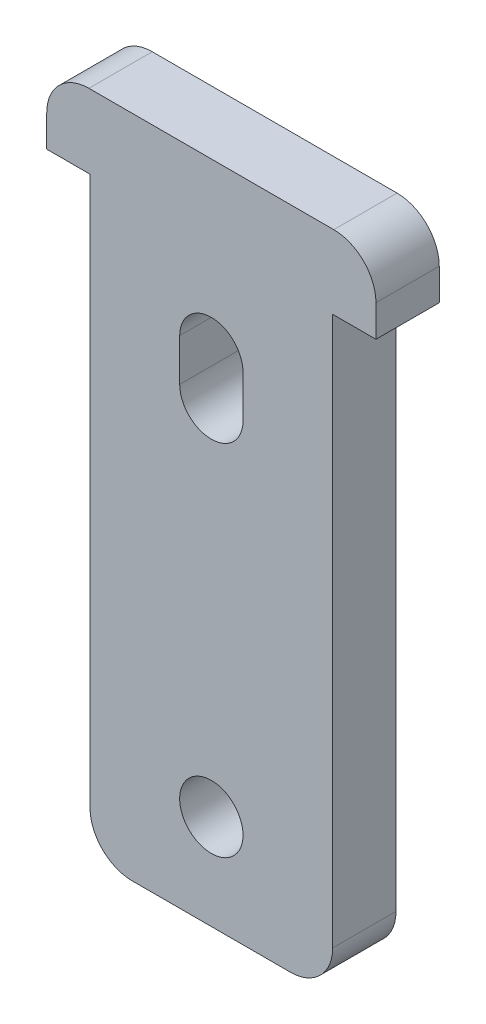
SolidWorks part; units mm, degrees
ref_plane "Plano frontal" through (0, 0, 0) normal (0, 0, 1) x (1, 0, 0)
ref_plane "Plano superior" through (0, 0, 0) normal (0, 1, 0) x (1, 0, 0)
ref_plane "Plano direito" through (0, 0, 0) normal (1, 0, 0) x (0, 0, -1)
sketch "Esboço1" plane through (0, 0, 0) normal (0, 0, 1) x (1, 0, 0)
  line L0 (11.5, 28) -> (13.55, 28)
  line L1 (0, 0) -> (11.5, 0)
  line L2 (0, 0) -> (0, 28)
  line L3 (4.25, 21.5) -> (4.25, 23.5)
  line L4 (11.5, 0) -> (11.5, 28)
  line L5 (-2.05, 28) -> (0, 28)
  line L6 (-2.05, 28) -> (-2.05, 31.5)
  line L7 (-2.05, 31.5) -> (13.55, 31.5)
  line L8 (13.55, 28) -> (13.55, 31.5)
  line L9 (7.25, 23.5) -> (7.25, 21.5)
  circle A0 centre (5.75, 4.5) radius 1.5
  arc A1 (7.25, 23.5) -> (4.25, 23.5) centre (5.75, 23.5) ccw
  arc A2 (4.25, 21.5) -> (7.25, 21.5) centre (5.75, 21.5) ccw
  dimension "D5" = 3
  dimension "D1" = 31.5
  dimension "D2" = 11.5
  dimension "D3" = 15.6
  dimension "D4" = 3.5
  dimension "D6" = 5.75
  dimension "D7" = 4.5
  dimension "D8" = 2
  dimension "D9" = 17
extrude "Ressalto-extrusão1" add sketch "Esboço1" along normal blind 3
fillet "Filete1" radius 2 2 edges at (-2.05, 31.5, 1.5) (13.55, 31.5, 1.5)
fillet "Filete2" radius 2 2 edges at (11.5, 0, 1.5) (0, 0, 1.5)
